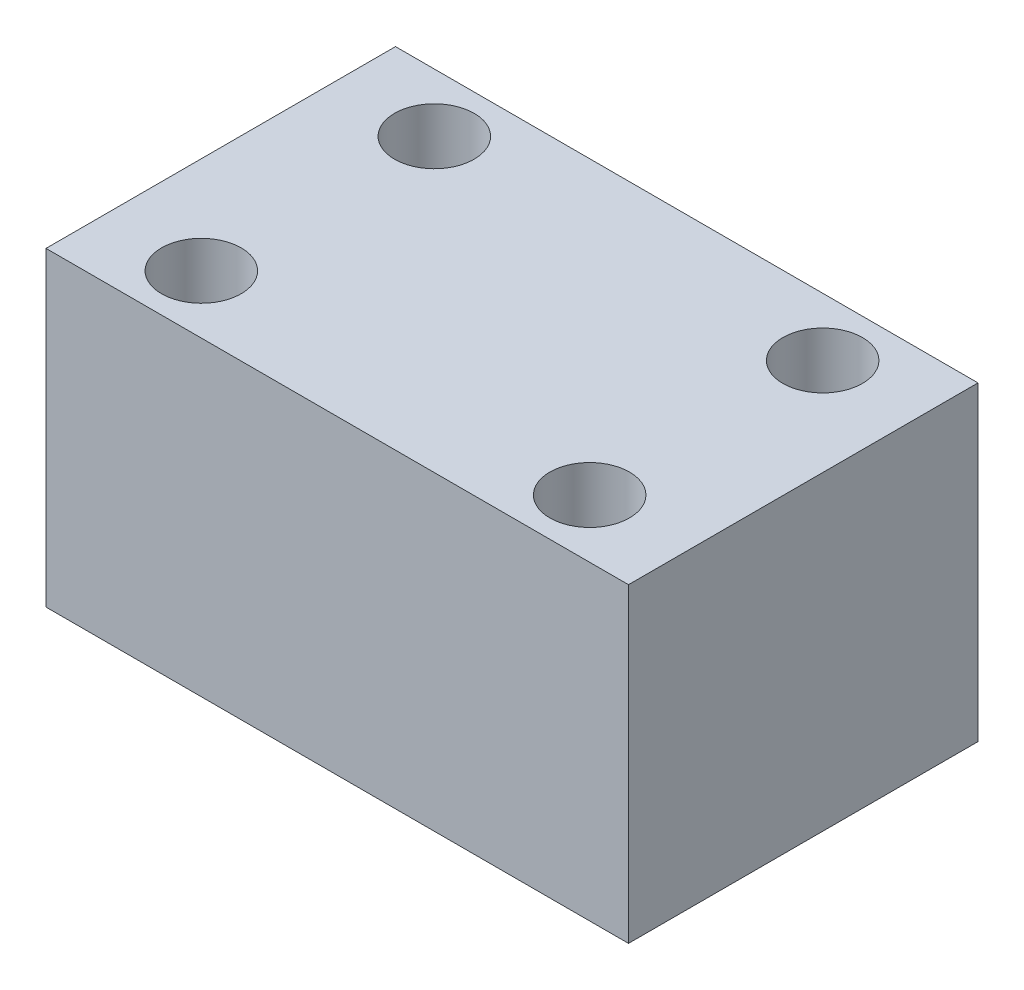
SolidWorks part; units mm, degrees
ref_plane "Front Plane" through (0, 0, 0) normal (0, 0, 1) x (1, 0, 0)
ref_plane "Top Plane" through (0, 0, 0) normal (0, 1, 0) x (1, 0, 0)
ref_plane "Right Plane" through (0, 0, 0) normal (1, 0, 0) x (0, 0, -1)
sketch "Sketch2" plane through (0, 0, 0) normal (0, 0, 1) x (1, 0, 0)
  line L0 (0, 0) -> (30, 0)
  line L1 (30, 0) -> (30, 16)
  line L2 (30, 16) -> (0, 16)
  line L3 (0, 16) -> (0, 0)
  dimension "D1" = 30
  dimension "D2" = 16
extrude "Boss-Extrude1" add sketch "Sketch2" against normal blind 18
sketch "Sketch3" plane through (0, 16, 0) normal (0, 1, 0) x (1, 0, 0)
  line L0 (30, 0) -> (0, 0) construction
  circle A0 centre (25, 15) radius 2.05
  circle A1 centre (25, 3) radius 2.05
  circle A2 centre (5, 3) radius 2.05
  circle A3 centre (5, 15) radius 2.05
  dimension "D1" = 4.1
  dimension "D2" = 4.1
  dimension "D3" = 4.1
  dimension "D4" = 4.1
  dimension "D5" = 12
  dimension "D6" = 12
  dimension "D7" = 20
  dimension "D8" = 5
  dimension "D9" = 3
  dimension "D10" = 3
extrude "Cut-Extrude1" cut sketch "Sketch3" against normal blind 16
